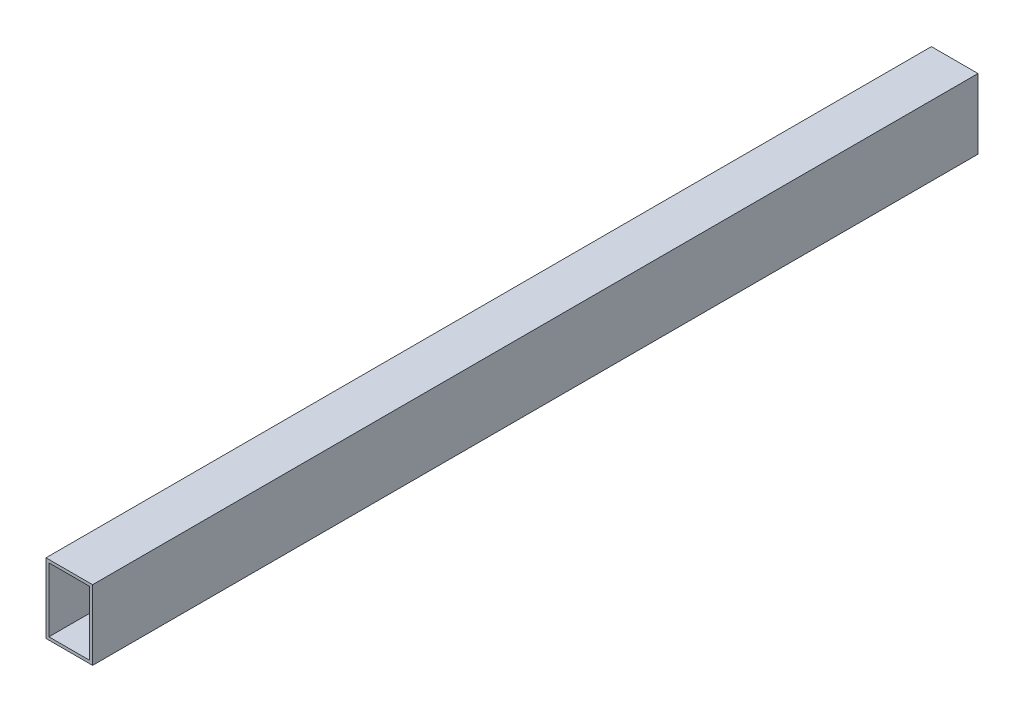
SolidWorks part; units mm, degrees
ref_plane "Front Plane" through (0, 0, 0) normal (0, 0, 1) x (1, 0, 0)
ref_plane "Top Plane" through (0, 0, 0) normal (0, 1, 0) x (1, 0, 0)
ref_plane "Right Plane" through (0, 0, 0) normal (1, 0, 0) x (0, 0, -1)
sketch "Sketch1" plane through (0, 0, 0) normal (0, 0, 1) x (1, 0, 0)
  line L0 (0, 38.1) -> (0, 34.925) construction
  line L1 (-25.4, 38.1) -> (25.4, 38.1)
  line L2 (-25.4, 38.1) -> (-25.4, -38.1)
  line L3 (-25.4, -38.1) -> (25.4, -38.1)
  line L4 (25.4, 38.1) -> (25.4, -38.1)
  line L5 (-25.4, 38.1) -> (25.4, -38.1) construction
  line L6 (-25.4, -38.1) -> (25.4, 38.1) construction
  line L7 (-22.225, 34.925) -> (22.225, 34.925)
  line L8 (-22.225, 34.925) -> (-22.225, -34.925)
  line L9 (-22.225, -34.925) -> (22.225, -34.925)
  line L10 (22.225, 34.925) -> (22.225, -34.925)
  line L11 (22.225, 0) -> (25.4, 0) construction
  line L12 (-22.225, 0) -> (-25.4, 0) construction
  line L13 (0, -34.925) -> (0, -38.1) construction
  point P0 (0, 0)
  dimension "D1" = 76.2
  dimension "D2" = 50.8
  dimension "D3" = 3.175
extrude "Boss-Extrude1" add sketch "Sketch1" along normal blind 965.2
sketch "Sketch2" plane through (0, 38.1, 0) normal (0, 1, 0) x (1, 0, 0)
  line L0 (-26.9875, -190.549) -> (26.9875, -190.549) construction
  line L1 (-25.4, 0) -> (25.4, 0)
  line L2 (-25.4, 0) -> (-25.4, -965.2)
  line L3 (-25.4, -965.2) -> (25.4, -965.2)
  line L4 (25.4, 0) -> (25.4, -965.2)
  line L5 (-26.4963, -703.2466) -> (26.4963, -703.2466) construction
  line L6 (0, -703.2466) -> (0, -190.549) construction
  line L7 (0, 0) -> (0, -190.549) construction
  line L8 (-74.6125, -402.6047) -> (-73.6301, -528.6965) construction
  line L9 (-74.1213, -465.6506) -> (-23.8125, -465.6506) construction
  line L10 (-23.8125, -465.6506) -> (26.9875, -465.6506) construction
  point P5 (25.4, -965.2)
  point P20 (0, 0)
  dimension "D1" = 190.549
  dimension "D2" = 512.6976
  dimension "D3" = 126.0917
  dimension "D4" = 50.3088
  dimension "D5" = 50.8
  dimension "D6" = 53.975
  dimension "D7" = 52.9926
  dimension "D8" = 275.1016
ref_plane "Plane1" through (25.4, 0, 0) normal (1, 0, 0) x (0, 0, -1)
sketch "Sketch4" plane through (25.4, 0, 0) normal (1, 0, 0) x (0, 0, -1)
  line L0 (-703.2466, 38.1) -> (-703.2466, 0) construction
  line L1 (-703.2466, 38.1) -> (-190.549, 38.1) construction
  line L2 (-190.549, 38.1) -> (-190.549, 0) construction
  line L3 (0, 38.1) -> (-190.549, 38.1) construction
  line L4 (-190.549, 0) -> (0, 0) construction
  line L5 (0, -38.1) -> (0, 38.1) construction
  line L6 (-190.549, 0) -> (-703.2466, 0) construction
  circle A0 centre (-703.2466, 0) radius 14.224
  circle A1 centre (-190.549, 0) radius 14.224
  dimension "D1" = 28.448
  dimension "D2" = 512.6976
  dimension "D3" = 190.549
